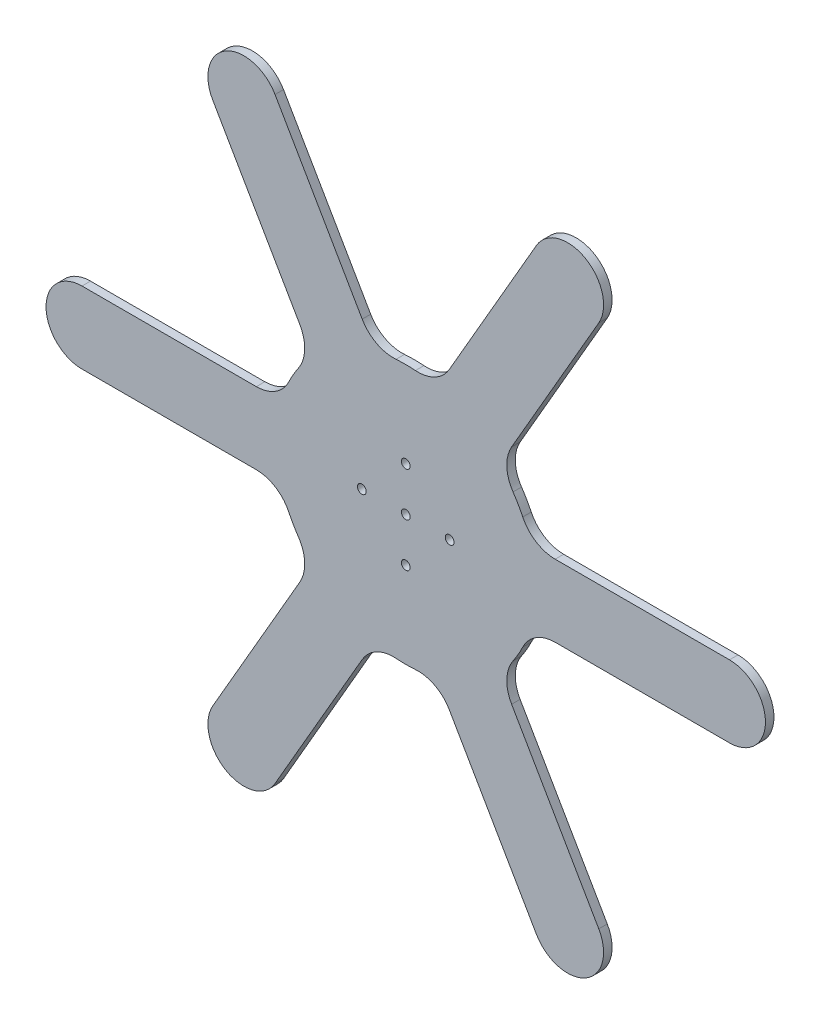
SolidWorks part; units mm, degrees
ref_plane "Alzado" through (0, 0, 0) normal (0, 0, 1) x (1, 0, 0)
ref_plane "Planta" through (0, 0, 0) normal (0, 1, 0) x (1, 0, 0)
ref_plane "Vista lateral" through (0, 0, 0) normal (1, 0, 0) x (0, 0, -1)
sketch "Croquis1" plane through (0, 0, 0) normal (0, 0, 1) x (1, 0, 0)
  line L0 (-52.7536, 12.7) -> (-114.3, 12.7)
  line L1 (0, 0) -> (-114.3, 0) construction
  line L2 (-52.7536, -12.7) -> (-114.3, -12.7)
  line L3 (-15.3783, 52.036) -> (-46.1515, 105.3367)
  line L4 (-37.3753, 39.336) -> (-68.1485, 92.6367)
  line L5 (37.3753, 39.336) -> (68.1485, 92.6367)
  line L6 (15.3783, 52.036) -> (46.1515, 105.3367)
  line L7 (52.7536, -12.7) -> (114.3, -12.7)
  line L8 (52.7536, 12.7) -> (114.3, 12.7)
  line L9 (15.3783, -52.036) -> (46.1515, -105.3367)
  line L10 (37.3753, -39.336) -> (68.1485, -92.6367)
  line L11 (-37.3753, -39.336) -> (-68.1485, -92.6367)
  line L12 (-15.3783, -52.036) -> (-46.1515, -105.3367)
  circle A0 centre (0, 0) radius 127 construction
  circle A1 centre (0, 0) radius 15.5 construction
  circle A2 centre (0, 0) radius 1.55
  circle A3 centre (0, 15.5) radius 1.55
  circle A4 centre (15.5, 0) radius 1.55
  circle A5 centre (0, -15.5) radius 1.55
  circle A6 centre (-15.5, 0) radius 1.55
  circle A7 centre (0, 0) radius 45.85 construction
  arc A8 (-41.3109, 19.8905) -> (-52.7536, 12.7) centre (-52.7536, 25.4) cw
  arc A9 (-114.3, 12.7) -> (-114.3, -12.7) centre (-114.3, 0) ccw
  arc A10 (-41.3109, -19.8905) -> (-52.7536, -12.7) centre (-52.7536, -25.4) ccw
  arc A11 (-41.3109, 19.8905) -> (-37.8811, 25.831) centre (0, 0) cw
  arc A12 (-3.4297, 45.7215) -> (-15.3783, 52.036) centre (-4.3798, 58.386) cw
  arc A13 (-3.4297, 45.7215) -> (3.4297, 45.7215) centre (0, 0) cw
  arc A14 (-46.1515, 105.3367) -> (-68.1485, 92.6367) centre (-57.15, 98.9867) ccw
  arc A15 (-37.8811, 25.831) -> (-37.3753, 39.336) centre (-48.3738, 32.986) ccw
  arc A16 (37.8811, 25.831) -> (37.3753, 39.336) centre (48.3738, 32.986) cw
  arc A17 (37.8811, 25.831) -> (41.3109, 19.8905) centre (0, 0) cw
  arc A18 (68.1485, 92.6367) -> (46.1515, 105.3367) centre (57.15, 98.9867) ccw
  arc A19 (3.4297, 45.7215) -> (15.3783, 52.036) centre (4.3798, 58.386) ccw
  arc A20 (41.3109, -19.8905) -> (52.7536, -12.7) centre (52.7536, -25.4) cw
  arc A21 (41.3109, -19.8905) -> (37.8811, -25.831) centre (0, 0) cw
  arc A22 (114.3, -12.7) -> (114.3, 12.7) centre (114.3, 0) ccw
  arc A23 (41.3109, 19.8905) -> (52.7536, 12.7) centre (52.7536, 25.4) ccw
  arc A24 (3.4297, -45.7215) -> (15.3783, -52.036) centre (4.3798, -58.386) cw
  arc A25 (3.4297, -45.7215) -> (-3.4297, -45.7215) centre (0, 0) cw
  arc A26 (46.1515, -105.3367) -> (68.1485, -92.6367) centre (57.15, -98.9867) ccw
  arc A27 (37.8811, -25.831) -> (37.3753, -39.336) centre (48.3738, -32.986) ccw
  arc A28 (-37.8811, -25.831) -> (-37.3753, -39.336) centre (-48.3738, -32.986) cw
  arc A29 (-37.8811, -25.831) -> (-41.3109, -19.8905) centre (0, 0) cw
  arc A30 (-68.1485, -92.6367) -> (-46.1515, -105.3367) centre (-57.15, -98.9867) ccw
  arc A31 (-3.4297, -45.7215) -> (-15.3783, -52.036) centre (-4.3798, -58.386) ccw
  point P16 (0, 0)
  point P20 (-114.3, 12.7)
  point P26 (0, 0)
  point P27 (-37.8811, 25.4)
  point P28 (-112.2417, -12.5321)
  point P38 (-114.3, -12.7)
  point P47 (-114.1856, -12.7)
  point P49 (-52.7536, -12.7)
  point P58 (-41.3109, -19.8905)
  point P84 (0, 0)
  dimension "D1" = 254
  dimension "D2" = 31
  dimension "D3" = 3.1
  dimension "D4" = 3.1
  dimension "D6" = 91.7
  dimension "D7" = 12.7
  dimension "D5" = 4
  dimension "D8" = 6
extrude "Saliente-Extruir1" add sketch "Croquis1" along normal mid plane 3
